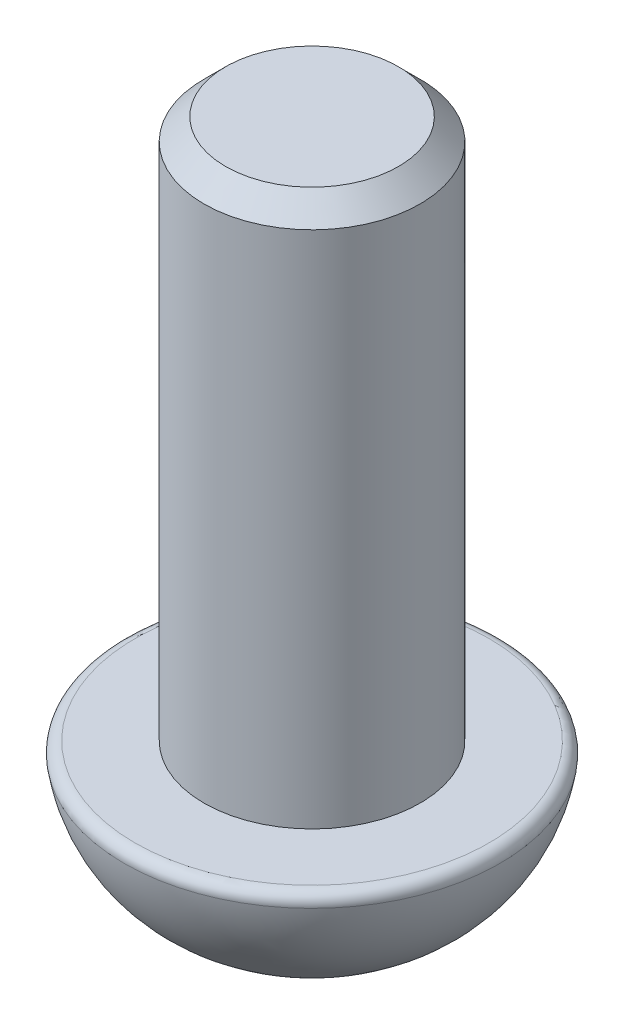
SolidWorks part; units mm, degrees
material "Stainless Steel (ferritic)"
ref_plane "Front Plane" through (0, 0, 0) normal (0, 0, 1) x (1, 0, 0)
ref_plane "Top Plane" through (0, 0, 0) normal (0, 1, 0) x (1, 0, 0)
ref_plane "Right Plane" through (0, 0, 0) normal (1, 0, 0) x (0, 0, -1)
sketch "Sketch1" plane through (0, 0, 0) normal (0, 1, 0) x (1, 0, 0)
  circle A0 centre (0, 0) radius 1.75
  dimension "D1" = 3.5
extrude "Boss-Extrude1" add sketch "Sketch1" along normal blind 1.3
sketch "Sketch2" plane through (0, 1.3, 0) normal (0, 1, 0) x (1, 0, 0)
  circle A0 centre (0, 0) radius 1
extrude "Boss-Extrude2" add sketch "Sketch2" along normal blind 5
sketch "Sketch3" plane through (0, 0, 0) normal (0, -1, 0) x (1, 0, 0)
  line L1 (0, -0.7506) -> (0.65, -0.3753)
  line L2 (0.65, -0.3753) -> (0.65, 0.3753)
  line L3 (0.65, 0.3753) -> (0, 0.7506)
  line L4 (0, 0.7506) -> (-0.65, 0.3753)
  line L5 (-0.65, 0.3753) -> (-0.65, -0.3753)
  line L6 (-0.65, -0.3753) -> (0, -0.7506)
  circle A0 centre (0, 0) radius 0.65 construction
  dimension "D1" = 1.3
extrude "Cut-Extrude1" cut sketch "Sketch3" against normal blind 0.8
chamfer "Chamfer1" distance 0.2 angle 45 1 edges at (0, 6.3, 1)
cosmetic thread "Cosmetic Thread1" parameters "D2"=1.548
sketch "Sketch4" plane through (0, 0, 0) normal (1, 0, 0) x (0, 0, -1)
  line L0 (1.75, 1.3) -> (-1.75, 1.3) construction
  line L1 (0.7506, 0) -> (0.3753, 0) construction
  line L2 (-1.75, 0) -> (1.75, 0) construction
  line L3 (1.75, 1.3) -> (1.75, 0)
  line L4 (1.75, 0) -> (0.7506, 0)
  arc A0 (1.75, 1.3) -> (0.7506, 0) centre (0.2545, 1.4156) cw
revolve "Cut-Revolve1" cut sketch "Sketch4" angle 360 about axis through (0, 6.3, 0) along (0, -1, 0)
fillet "Fillet1" radius 0.1 1 edges at (0, 1.3, 1.75)
